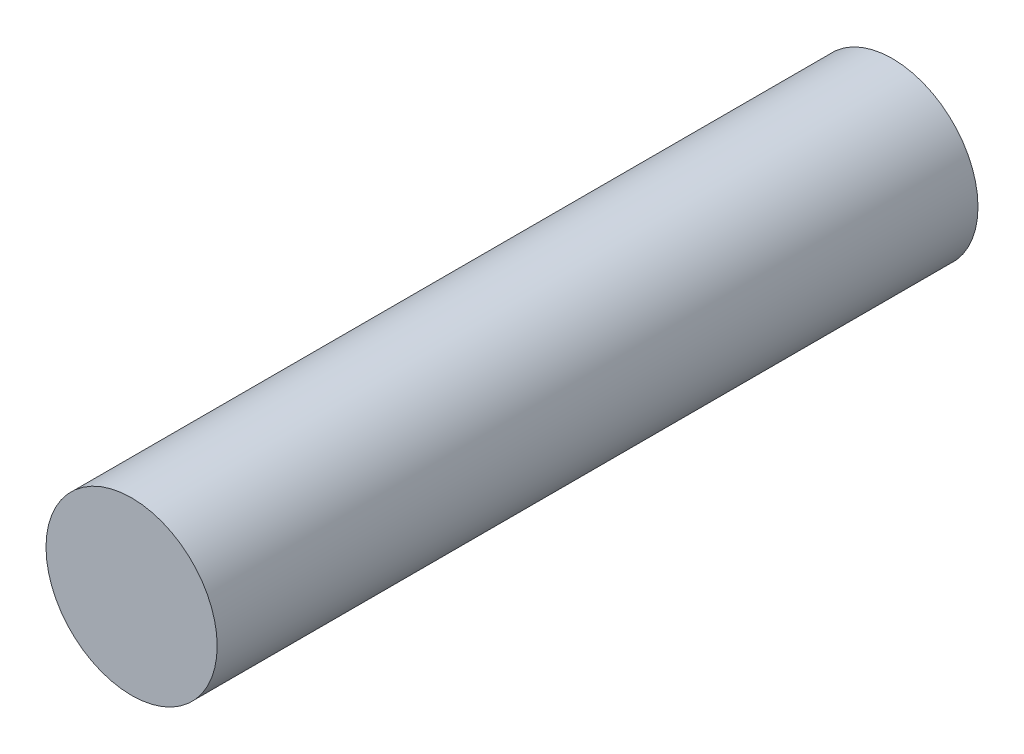
SolidWorks part; units mm, degrees
ref_plane "前视基准面" through (0, 0, 0) normal (0, 0, 1) x (1, 0, 0)
ref_plane "上视基准面" through (0, 0, 0) normal (0, 1, 0) x (1, 0, 0)
ref_plane "右视基准面" through (0, 0, 0) normal (1, 0, 0) x (0, 0, -1)
sketch "草图1" plane through (0, 0, 0) normal (0, 0, 1) x (1, 0, 0)
  circle A0 centre (0, 0) radius 4.5
  dimension "D1" = 9
extrude "凸台-拉伸1" add sketch "草图1" along normal blind 40
